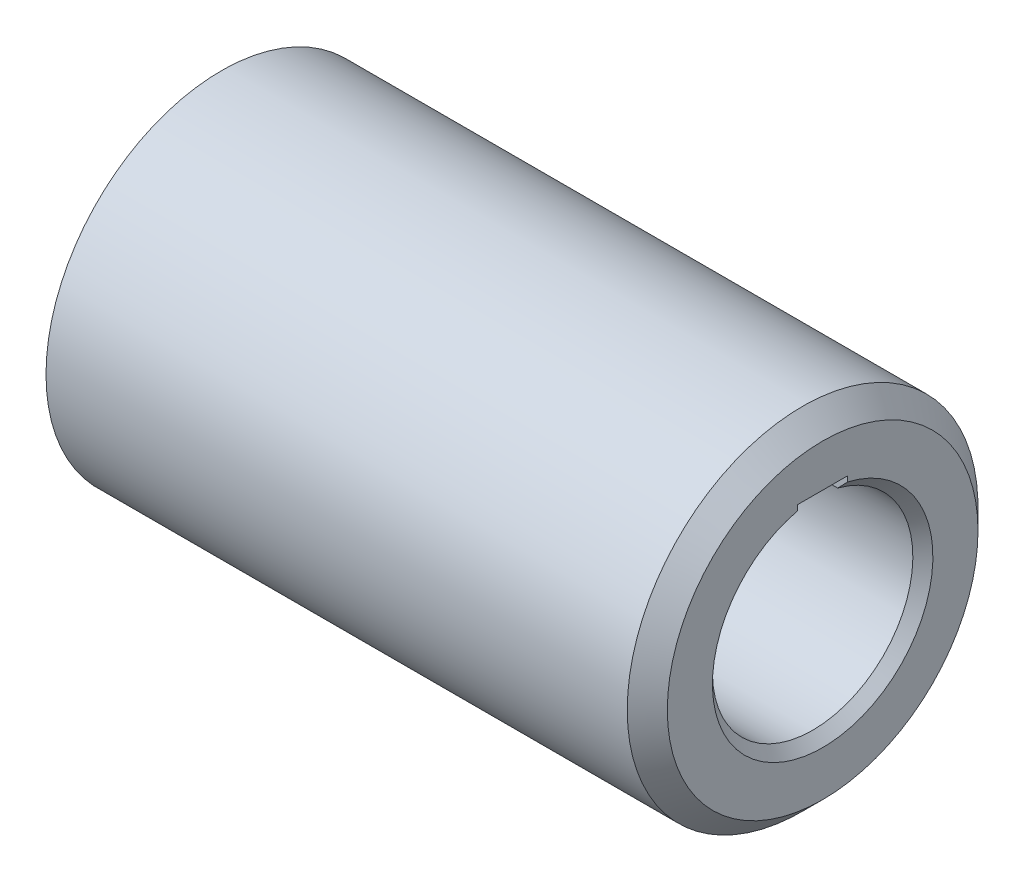
SolidWorks part; units mm, degrees
ref_plane "Front Plane" through (0, 0, 0) normal (0, 0, 1) x (1, 0, 0)
ref_plane "Top Plane" through (0, 0, 0) normal (0, 1, 0) x (1, 0, 0)
ref_plane "Right Plane" through (0, 0, 0) normal (1, 0, 0) x (0, 0, -1)
sketch "Sketch1" plane through (0, 0, 0) normal (1, 0, 0) x (0, 0, -1)
  circle A0 centre (0, 0) radius 11.1125
  dimension "D1" = 22.225
extrude "Boss-Extrude1" add sketch "Sketch1" along normal blind 38.1
sketch "Sketch2" plane through (38.1, 0, 0) normal (1, 0, 0) x (0, 0, -1)
  circle A0 centre (0, 0) radius 6.35
  dimension "D1" = 12.7
extrude "Cut-Extrude1" cut sketch "Sketch2" against normal blind 25.4
sketch "Sketch3" plane through (38.1, 0, 0) normal (1, 0, 0) x (0, 0, -1)
  line L0 (1.5875, 5.5562) -> (1.5875, 7.1438)
  line L1 (1.5875, 5.5562) -> (-1.5875, 5.5562)
  line L2 (1.5875, 7.1438) -> (-1.5875, 7.1437)
  line L3 (-1.5875, 5.5562) -> (-1.5875, 7.1437)
  line L4 (1.5875, 5.5562) -> (-1.5875, 7.1437) construction
  line L5 (1.5875, 7.1438) -> (-1.5875, 5.5562) construction
  circle A0 centre (0, 0) radius 6.35 construction
  circle A1 centre (0, 0) radius 7.1438 construction
  point P5 (0, 6.35)
  dimension "D1" = 14.2875
  dimension "D2" = 3.175
  dimension "D3" = 6.35
  dimension "D4" = 1.5875
extrude "Cut-Extrude2" cut sketch "Sketch3" against normal blind 25.4
chamfer "Chamfer2" distance 0.635 distance2 0.635 1 edges at (38.1, -6.35, 0)
chamfer "Chamfer3" distance 1.27 angle 45 1 edges at (38.1, 0, -11.1125)
